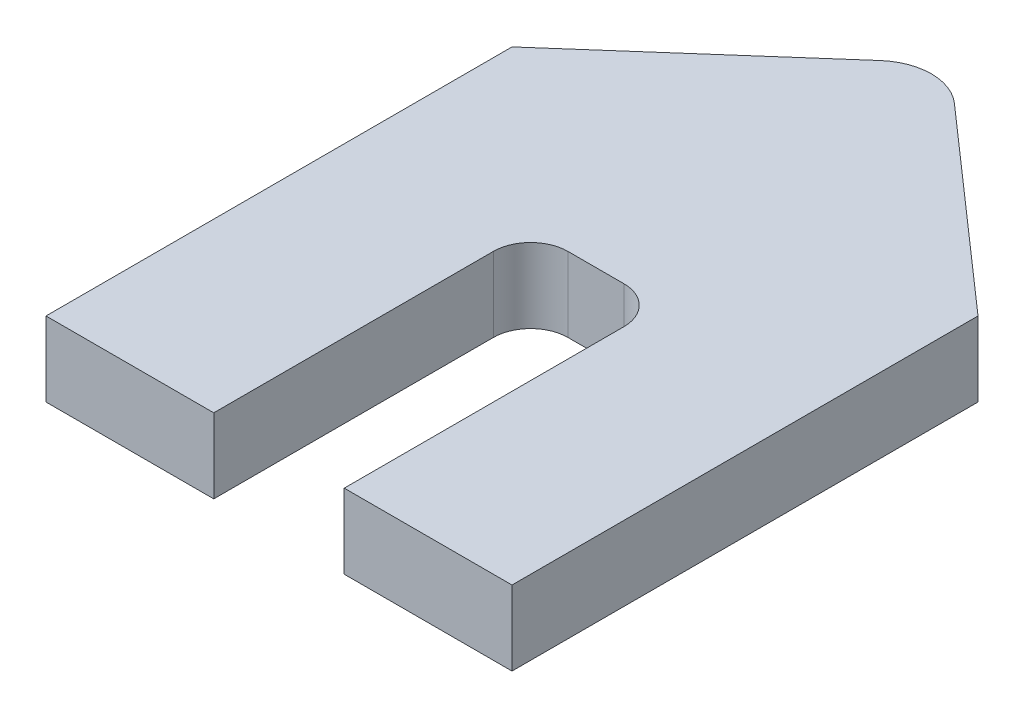
SolidWorks part; units mm, degrees
material "2024 Alloy"
ref_plane "Front Plane" through (0, 0, 0) normal (0, 0, 1) x (1, 0, 0)
ref_plane "Top Plane" through (0, 0, 0) normal (0, 1, 0) x (1, 0, 0)
ref_plane "Right Plane" through (0, 0, 0) normal (1, 0, 0) x (0, 0, -1)
sketch "Sketch1" plane through (0, 0, 0) normal (0, 1, 0) x (1, 0, 0)
  line L0 (-12.5, 12.5) -> (0, 23.4955) construction
  line L1 (-12.5, -12.5) -> (12.5, -12.5)
  line L2 (-12.5, -12.5) -> (-12.5, 12.5)
  line L3 (-12.5, 12.5) -> (12.5, 12.5) construction
  line L4 (12.5, -12.5) -> (12.5, 12.5)
  line L5 (-12.5, -12.5) -> (12.5, 12.5) construction
  line L6 (-12.5, 12.5) -> (12.5, -12.5) construction
  line L7 (0, 23.4955) -> (12.5, 12.5) construction
  line L8 (-12.5, 12.5) -> (-1.9814, 21.7525)
  line L9 (12.5, 12.5) -> (1.9814, 21.7525)
  arc A0 (-1.9814, 21.7525) -> (1.9814, 21.7525) centre (0, 19.5) cw
  point P0 (0, 0)
  point P11 (0, 22.5)
  dimension "D3" = 3
  dimension "D1" = 25
  dimension "D2" = 10
extrude "Boss-Extrude1" add sketch "Sketch1" along normal mid plane 4
sketch "Sketch2" plane through (0, 2, 0) normal (0, 1, 0) x (1, 0, 0)
  line L0 (-12.5, -12.5) -> (12.5, -12.5) construction
  line L1 (-3.5, -12.5) -> (3.5, -12.5)
  line L2 (-3.5, -12.5) -> (-3.5, 4.5)
  line L3 (-3.5, 4.5) -> (3.5, 4.5)
  line L4 (3.5, -12.5) -> (3.5, 4.5)
  point P6 (0, -12.5)
  dimension "D1" = 7
  dimension "D2" = 17
extrude "Cut-Extrude1" cut sketch "Sketch2" against normal up to next
fillet "Fillet1" radius 2 2 edges at (3.5, 0, -4.5) (-3.5, 0, -4.5)
